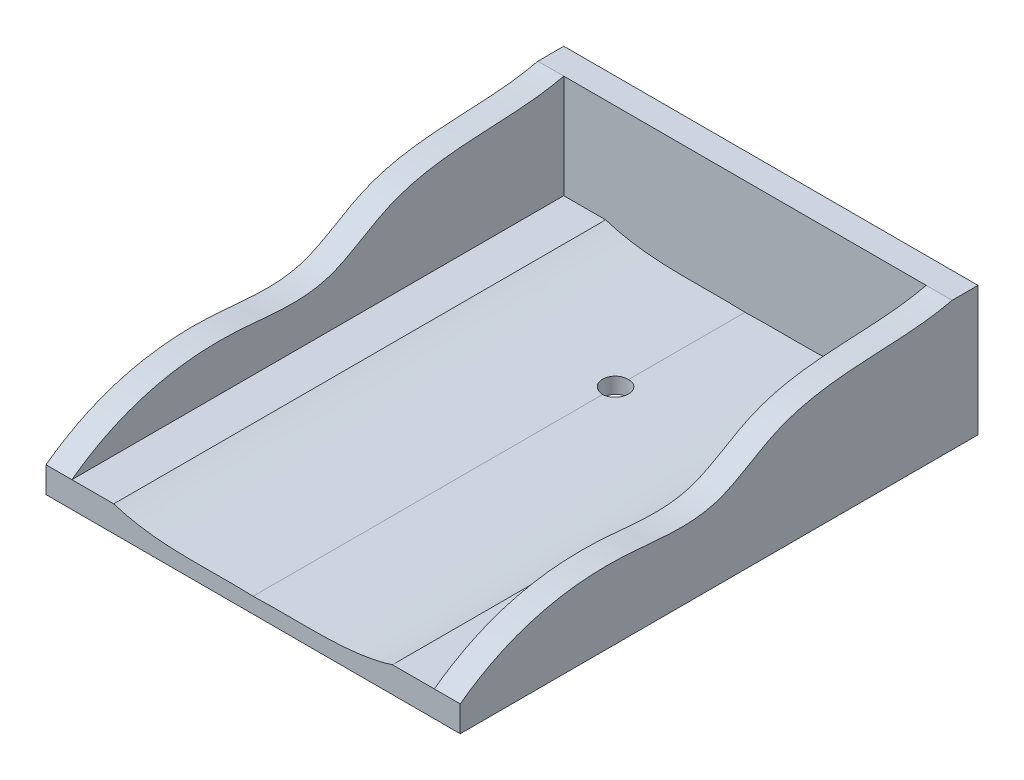
SolidWorks part; units mm, degrees
ref_plane "Alzado" through (0, 0, 0) normal (0, 0, 1) x (1, 0, 0)
ref_plane "Planta" through (0, 0, 0) normal (0, 1, 0) x (1, 0, 0)
ref_plane "Vista lateral" through (0, 0, 0) normal (1, 0, 0) x (0, 0, -1)
sketch "Croquis2" plane through (0, 0, 0) normal (0, 1, 0) x (1, 0, 0)
  line L1 (-80, -100) -> (80, -100)
  line L2 (-80, -100) -> (-80, 100)
  line L3 (-80, 100) -> (80, 100)
  line L4 (80, -100) -> (80, 100)
  line L5 (-80, -100) -> (80, 100) construction
  line L6 (-80, 100) -> (80, -100) construction
  point P0 (0, 0)
  dimension "D1" = 200
  dimension "D2" = 160
extrude "Saliente-Extruir1" add sketch "Croquis2" along normal blind 10
sketch "Croquis3" plane through (0, 0, 100) normal (0, 0, 1) x (1, 0, 0)
  line L0 (-80, 10) -> (80, 10) construction
  line L1 (-53.8268, 10) -> (53.8268, 10)
  spline S0 degree 3 poles (-53.8268, 10) (-36.4733, 4.4266) (-17.8285, 6.7923) (0, 5.9904) knots 0 0 0 0 1 1 1 1
  spline S1 degree 3 poles (53.8268, 10) (36.4733, 4.4266) (17.8285, 6.7923) (0, 5.9904) knots 0 0 0 0 1 1 1 1
extrude "Cortar-Extruir1" cut sketch "Croquis3" against normal through all
sketch "Croquis4" plane through (0, 0, -100) normal (0, 0, -1) x (-1, 0, 0)
  line L0 (-80, 10) -> (-80, 50)
  line L1 (-80, 50) -> (80, 50)
  line L2 (80, 50) -> (80, 10)
  line L3 (80, 10) -> (80, 0)
  line L4 (80, 0) -> (-80, 0)
  line L5 (-80, 0) -> (-80, 10)
  dimension "D1" = 40
extrude "Saliente-Extruir2" add sketch "Croquis4" against normal blind 10
sketch "Croquis5" plane through (80, 0, 0) normal (1, 0, 0) x (0, 0, -1)
  line L0 (-100, 10) -> (90, 10)
  line L1 (90, 10) -> (90, 50)
  spline S0 degree 3 poles (-100, 10) (-81.1441, 23.9098) (-47.8832, 31.723) (-3.1748, 22.9238) (33.1089, 51.133) (68.3711, 44.7808) (90, 50) knots 0 0 0 0 0.338396 0.520486 0.646796 1 1 1 1
extrude "Saliente-Extruir3" add sketch "Croquis5" against normal blind 10
mirror "Simetría1" about plane through (0, 0, 0) normal (1, 0, 0) of "Saliente-Extruir3"
sketch "Croquis6" plane through (0, 0, 0) normal (0, -1, 0) x (1, 0, 0)
  line L0 (80, -100) -> (-80, -100) construction
  circle A0 centre (0, -40) radius 5
  dimension "D1" = 10
  dimension "D2" = 60
extrude "Cortar-Extruir2" cut sketch "Croquis6" against normal through all
